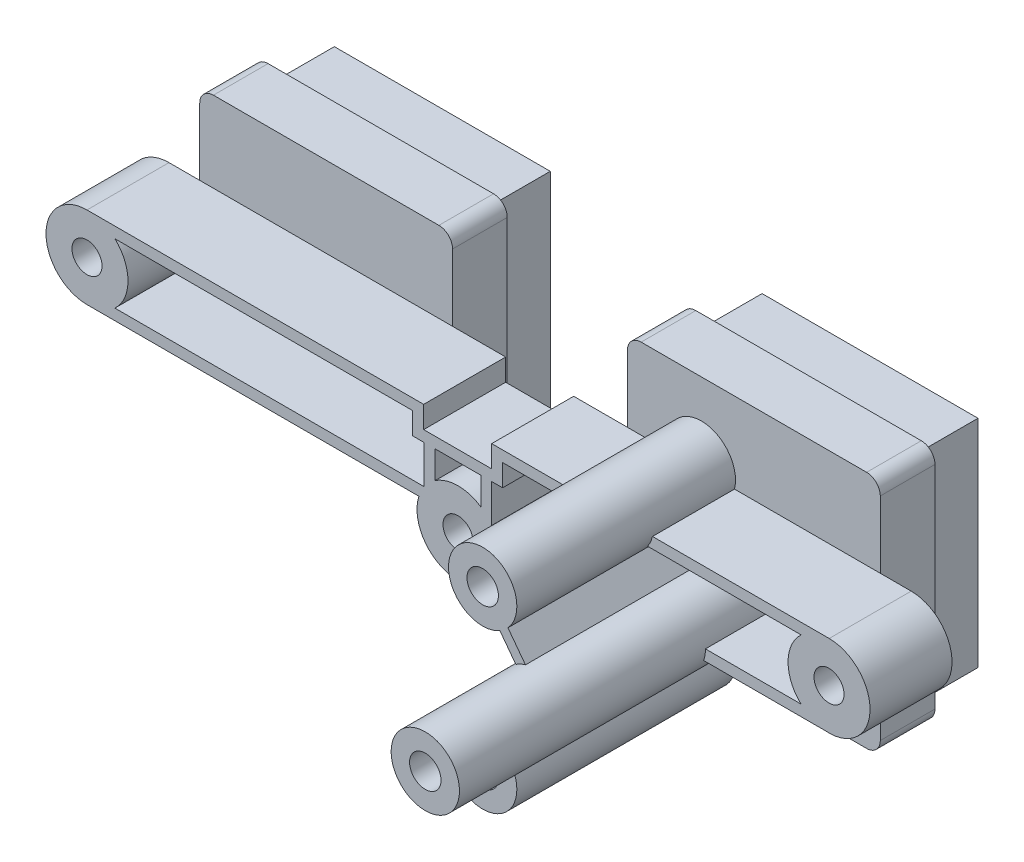
SolidWorks part; units mm, degrees
ref_plane "Plan de face" through (0, 0, 0) normal (0, 0, 1) x (1, 0, 0)
ref_plane "Plan de dessus" through (0, 0, 0) normal (0, 1, 0) x (1, 0, 0)
ref_plane "Plan de droite" through (0, 0, 0) normal (1, 0, 0) x (0, 0, -1)
sketch "Esquisse1" plane through (0, 0, 0) normal (0, 0, 1) x (1, 0, 0)
  circle A0 centre (27.15, 42.3987) radius 1.1 construction
  circle A1 centre (0, 38.4987) radius 1.1 construction
  circle A2 centre (-27.15, 42.3987) radius 1.1 construction
  circle A3 centre (27.15, 42.3987) radius 1.1
  circle A4 centre (0, 38.4987) radius 1.1
  circle A5 centre (-27.15, 42.3987) radius 1.1
  circle A6 centre (-27.15, 42.3987) radius 3
  circle A7 centre (0, 38.4987) radius 3
  circle A8 centre (27.15, 42.3987) radius 3
  dimension "D1" = 6
extrude "Extrusion1" add sketch "Esquisse1" along normal blind 6
sketch "Esquisse2" plane through (0, 0, 6) normal (0, 0, 1) x (1, 0, 0)
  line L1 (-27.15, 45.3987) -> (-2.5137, 45.3987)
  line L2 (-27.15, 45.3987) -> (-27.15, 44.5987)
  line L3 (-27.15, 44.5987) -> (-3.3137, 44.5987)
  line L4 (-2.5137, 45.3987) -> (-2.5137, 44.5987)
  line L5 (-27.15, 39.3987) -> (-2.4718, 39.3987)
  line L6 (-27.15, 39.3987) -> (-27.15, 40.1987)
  line L7 (-27.15, 40.1987) -> (-2.4718, 40.1987)
  line L9 (2.2077, 39.4104) -> (27.4138, 39.4104)
  line L11 (2.4638, 40.2104) -> (27.4138, 40.2104)
  line L12 (27.4138, 39.4104) -> (27.4138, 40.2104)
  line L13 (2.4638, 45.3987) -> (27.1616, 45.3987)
  line L14 (2.4638, 45.3987) -> (2.4638, 44.7243)
  line L15 (3.2638, 44.5987) -> (27.1616, 44.5987)
  line L16 (27.1616, 45.3987) -> (27.1616, 44.5987)
  line L17 (-2.5137, 43.797) -> (2.4638, 43.797)
  line L19 (-1.6718, 42.997) -> (1.6638, 42.997)
  line L22 (-2.4718, 42.997) -> (-2.4718, 40.1987)
  line L23 (-2.4718, 39.3987) -> (-1.6718, 39.3987)
  line L24 (-1.6718, 42.997) -> (-1.6718, 39.3987)
  line L26 (2.4638, 42.997) -> (2.4638, 40.2104)
  line L27 (2.2077, 39.4104) -> (1.6638, 39.4104)
  line L28 (1.6638, 42.997) -> (1.6638, 39.4104)
  line L30 (-2.5137, 44.5987) -> (-2.5137, 43.797)
  line L31 (-2.4718, 42.997) -> (-3.3137, 42.997)
  line L32 (-3.3137, 44.5987) -> (-3.3137, 42.997)
  line L34 (2.4638, 44.7243) -> (2.4638, 43.797)
  line L35 (2.4638, 42.997) -> (3.2638, 42.997)
  line L36 (3.2638, 44.5987) -> (3.2638, 42.997)
  circle A0 centre (-27.15, 42.3987) radius 3 construction
  circle A1 centre (0, 38.4987) radius 3 construction
  circle A2 centre (27.15, 42.3987) radius 3 construction
  dimension "D1" = 0.8
  dimension "D2" = 0.8
  dimension "D3" = 0.8
  dimension "D4" = 0.8
  dimension "D5" = 0.8
  dimension "D6" = 0.8
  dimension "D7" = 0.8
  dimension "D8" = 0.8
  dimension "D9" = 0.8
  dimension "D10" = 0.8
extrude "Extrusion2" add sketch "Esquisse2" against normal blind 6
sketch "Esquisse3" plane through (0, 0, 0) normal (0, 0, -1) x (-1, 0, 0)
  line L0 (7.75, 34.4987) -> (23.55, 34.4987) construction
  line L1 (23.55, 34.4987) -> (23.55, 50.2987) construction
  line L2 (23.55, 50.2987) -> (7.75, 50.2987) construction
  line L3 (7.75, 50.2987) -> (7.75, 34.4987) construction
  line L4 (-7.75, 34.4987) -> (-7.75, 50.2987) construction
  line L5 (-23.55, 34.4987) -> (-7.75, 34.4987) construction
  line L6 (-23.55, 50.2987) -> (-23.55, 34.4987) construction
  line L7 (-7.75, 50.2987) -> (-23.55, 50.2987) construction
  line L8 (7.75, 34.4987) -> (23.55, 34.4987)
  line L9 (23.55, 34.4987) -> (23.55, 50.2987)
  line L10 (23.55, 50.2987) -> (7.75, 50.2987)
  line L11 (7.75, 50.2987) -> (7.75, 34.4987)
  line L12 (-7.75, 34.4987) -> (-7.75, 50.2987)
  line L13 (-23.55, 34.4987) -> (-7.75, 34.4987)
  line L14 (-23.55, 50.2987) -> (-23.55, 34.4987)
  line L15 (-7.75, 50.2987) -> (-23.55, 50.2987)
extrude "Extrusion3" add sketch "Esquisse3" along normal blind 8.5
sketch "Esquisse4" plane through (0, 0, 0) normal (0, 0, -1) x (-1, 0, 0)
  line L0 (7.4, 33.7987) -> (23.9, 33.7987) construction
  line L1 (24.9, 34.7987) -> (24.9, 51.2987) construction
  line L2 (24.9, 51.2987) -> (6.4, 51.2987) construction
  line L3 (6.4, 51.2987) -> (6.4, 34.7987) construction
  line L4 (-6.4, 34.7987) -> (-6.4, 51.2987) construction
  line L5 (-23.9, 33.7987) -> (-7.4, 33.7987) construction
  line L6 (-24.9, 51.2987) -> (-24.9, 34.7987) construction
  line L7 (-6.4, 51.2987) -> (-24.9, 51.2987) construction
  line L8 (7.4, 33.7987) -> (23.9, 33.7987)
  line L9 (24.9, 34.7987) -> (24.9, 50.2987)
  line L10 (23.9, 51.2987) -> (7.4, 51.2987)
  line L11 (6.4, 50.2987) -> (6.4, 34.7987)
  line L12 (-6.4, 34.7987) -> (-6.4, 50.2987)
  line L13 (-23.9, 33.7987) -> (-7.4, 33.7987)
  line L14 (-24.9, 50.2987) -> (-24.9, 34.7987)
  line L15 (-7.4, 51.2987) -> (-23.9, 51.2987)
  arc A0 (6.4, 34.7987) -> (7.4, 33.7987) centre (7.4, 34.7987) ccw construction
  arc A1 (23.9, 33.7987) -> (24.9, 34.7987) centre (23.9, 34.7987) ccw construction
  arc A2 (24.9, 50.2987) -> (23.9, 51.2987) centre (23.9, 50.2987) ccw construction
  arc A3 (7.4, 51.2987) -> (6.4, 50.2987) centre (7.4, 50.2987) ccw construction
  arc A4 (-7.4, 33.7987) -> (-6.4, 34.7987) centre (-7.4, 34.7987) ccw construction
  arc A5 (-24.9, 34.7987) -> (-23.9, 33.7987) centre (-23.9, 34.7987) ccw construction
  arc A6 (-23.9, 51.2987) -> (-24.9, 50.2987) centre (-23.9, 50.2987) ccw construction
  arc A7 (6.4, 34.7987) -> (7.4, 33.7987) centre (7.4, 34.7987) ccw
  arc A8 (23.9, 33.7987) -> (24.9, 34.7987) centre (23.9, 34.7987) ccw
  arc A9 (24.9, 50.2987) -> (23.9, 51.2987) centre (23.9, 50.2987) ccw
  arc A10 (7.4, 51.2987) -> (6.4, 50.2987) centre (7.4, 50.2987) ccw
  arc A11 (-7.4, 33.7987) -> (-6.4, 34.7987) centre (-7.4, 34.7987) ccw
  arc A12 (-24.9, 34.7987) -> (-23.9, 33.7987) centre (-23.9, 34.7987) ccw
  arc A13 (-23.9, 51.2987) -> (-24.9, 50.2987) centre (-23.9, 50.2987) ccw
  arc A14 (-6.4, 50.2987) -> (-7.4, 51.2987) centre (-7.4, 50.2987) ccw construction
  arc A15 (-6.4, 50.2987) -> (-7.4, 51.2987) centre (-7.4, 50.2987) ccw
extrude "Extrusion4" add sketch "Esquisse4" along normal blind 4
sketch "Esquisse5" plane through (0, 0, 0) normal (0, 0, 1) x (1, 0, 0)
  circle A0 centre (15.605, 40.2044) radius 2.5
  circle A1 centre (15.605, 40.2044) radius 1.15
  circle A2 centre (15.605, 40.2044) radius 1.15
  dimension "D2" = 5
  dimension "D1" = 0
extrude "Extrusion5" add sketch "Esquisse5" along normal blind 24
sketch "Esquisse6" plane through (0, 0, 0) normal (0, 0, 1) x (1, 0, 0)
  circle A0 centre (11.805, 46.0044) radius 2.5
  circle A1 centre (11.805, 34.4044) radius 1.15
  circle A2 centre (11.805, 34.4044) radius 1.15
  circle A3 centre (11.805, 46.0044) radius 1.15
  circle A4 centre (11.805, 46.0044) radius 1.15
  circle A5 centre (11.805, 46.0044) radius 1.15
  circle A6 centre (11.805, 46.0044) radius 1.15
  circle A7 centre (11.805, 34.4044) radius 2.5
  line M10 (7.4, 33.7987) -> (23.9, 33.7987)
  dimension "D4" = 5
  dimension "D1" = 0
  dimension "D2" = 0
  dimension "D3" = 0
extrude "Extrusion6" add sketch "Esquisse6" along normal blind 16 contours A7 A2 M10 | A7 A2 M10 | A0 A4
sketch "Esquisse7" plane through (0, 0, 16) normal (0, 0, 1) x (1, 0, 0)
  line L0 (12.5585, 36.4465) -> (14.2929, 38.6948)
  line L1 (14.2929, 38.6948) -> (14.882, 38.2404)
  line L2 (14.882, 38.2404) -> (12.955, 35.7424)
  line L3 (12.955, 34.4044) -> (12.955, 46.0044) construction
  line L4 (12.955, 35.7424) -> (12.5585, 36.4465)
  line L5 (13.3936, 44.669) -> (15.3207, 42.0994)
  line L6 (15.3207, 42.0994) -> (14.7143, 41.6446)
  line L7 (14.7143, 41.6446) -> (12.955, 43.9904)
  line L8 (12.955, 43.9904) -> (13.3936, 44.669)
extrude "Extrusion7" add sketch "Esquisse7" against normal up to surface (16 mm away) up to face at (16.647, 42.5434, 0)
